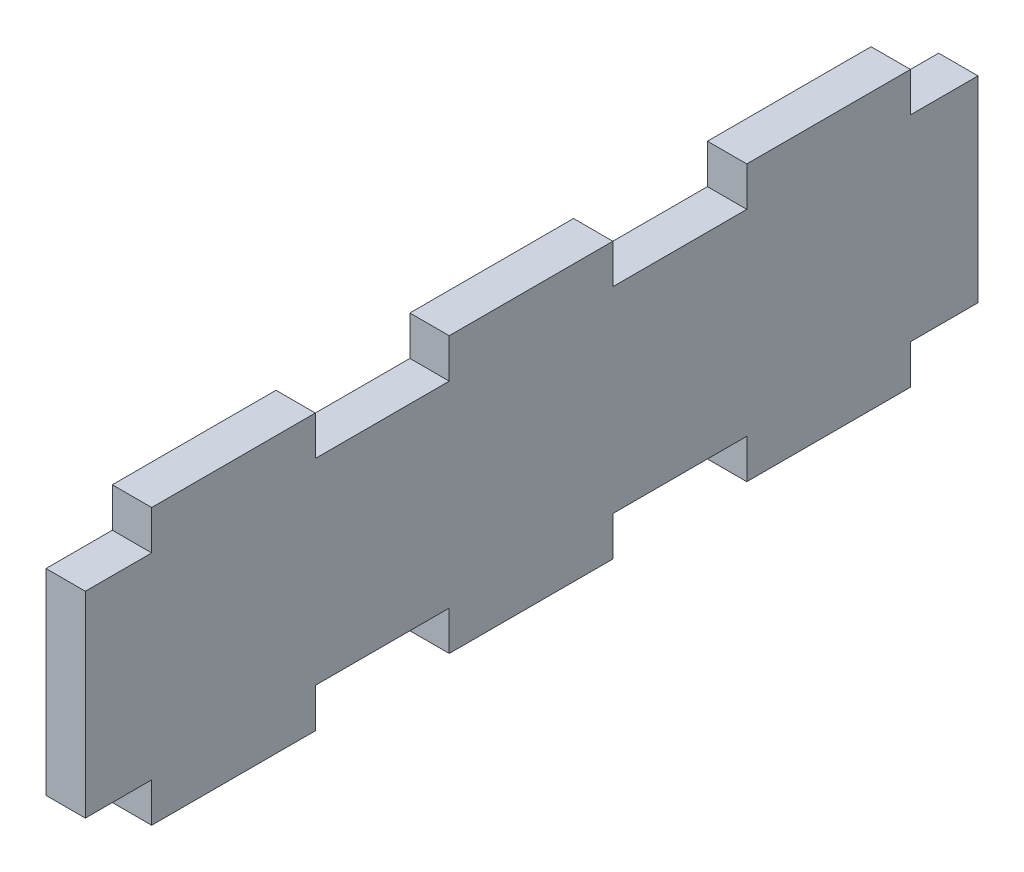
SolidWorks part; units mm, degrees
ref_plane "Front Plane" through (0, 0, 0) normal (0, 0, 1) x (1, 0, 0)
ref_plane "Top Plane" through (0, 0, 0) normal (0, 1, 0) x (1, 0, 0)
ref_plane "Right Plane" through (0, 0, 0) normal (1, 0, 0) x (0, 0, -1)
sketch "Sketch1" plane through (0, 0, 0) normal (1, 0, 0) x (0, 0, -1)
  line L1 (-18, -5.55) -> (18, -5.55)
  line L2 (-18, -5.55) -> (-18, 5.55)
  line L3 (-18, 5.55) -> (18, 5.55)
  line L4 (18, -5.55) -> (18, 5.55)
  line L5 (-18, -5.55) -> (18, 5.55) construction
  line L6 (-18, 5.55) -> (18, -5.55) construction
  point P0 (0, 0)
  dimension "D1" = 36
  dimension "D2" = 11.1
extrude "Boss-Extrude1" add sketch "Sketch1" along normal blind 1.5875
sketch "Sketch2" plane through (1.5875, 0, 0) normal (1, 0, 0) x (0, 0, -1)
  line L0 (18, 5.55) -> (-18, 5.55) construction
  line L1 (3.275, 5.55) -> (8.675, 5.55)
  line L2 (3.275, 5.55) -> (3.275, 3.9625)
  line L3 (3.275, 3.9625) -> (8.675, 3.9625)
  line L4 (8.675, 5.55) -> (8.675, 3.9625)
  line L5 (0, 0.8731) -> (0, -0.8731) construction
  line L6 (15.275, 5.55) -> (20.675, 5.55)
  line L7 (15.275, 5.55) -> (15.275, 3.9625)
  line L8 (15.275, 3.9625) -> (20.675, 3.9625)
  line L9 (20.675, 5.55) -> (20.675, 3.9625)
  line L10 (-8.725, 5.55) -> (-3.325, 5.55)
  line L11 (-8.725, 5.55) -> (-8.725, 3.9625)
  line L12 (-8.725, 3.9625) -> (-3.325, 3.9625)
  line L13 (-3.325, 5.55) -> (-3.325, 3.9625)
  line L14 (-20.725, 5.55) -> (-15.325, 5.55)
  line L15 (-20.725, 5.55) -> (-20.725, 3.9625)
  line L16 (-20.725, 3.9625) -> (-15.325, 3.9625)
  line L17 (-15.325, 5.55) -> (-15.325, 3.9625)
  dimension "D1" = 3.275
  dimension "D2" = 5.4
  dimension "D3" = 1.5875
  dimension "D4" = 2
  dimension "D5" = 3
extrude "Cut-Extrude1" cut sketch "Sketch2" against normal through all
mirror "Mirror1" about plane through (0, 0, 0) normal (0, 1, 0) of "Cut-Extrude1"
